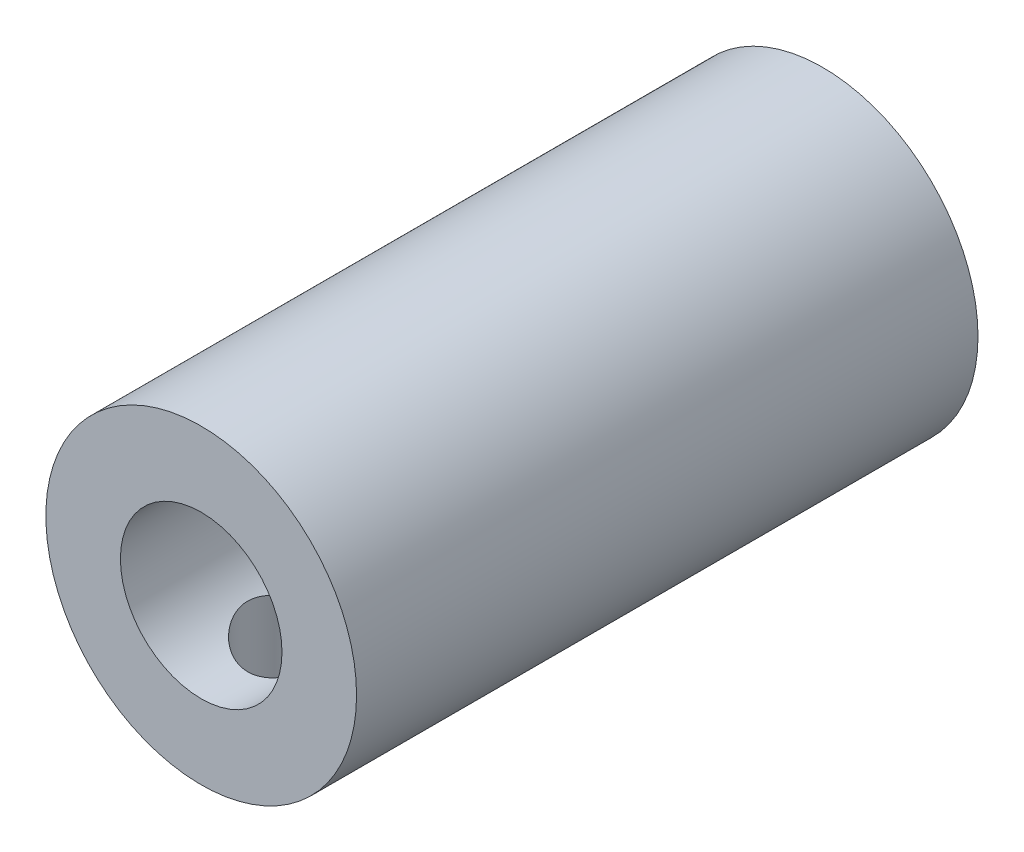
SolidWorks part; units mm, degrees
ref_plane "Front Plane" through (0, 0, 0) normal (0, 0, 1) x (1, 0, 0)
ref_plane "Top Plane" through (0, 0, 0) normal (0, 1, 0) x (1, 0, 0)
ref_plane "Right Plane" through (0, 0, 0) normal (1, 0, 0) x (0, 0, -1)
sketch "Sketch1" plane through (0, 0, 0) normal (0, 0, 1) x (1, 0, 0)
  line L0 (-100.533, 0) -> (100.533, 0) construction
  circle A0 centre (0, 0) radius 10
  point P4 (0, 0)
extrude "Boss-Extrude1" add sketch "Sketch1" along normal mid plane 40
sketch "Sketch5" plane through (0, 0, 0) normal (0, 0, 1) x (1, 0, 0)
  circle A0 centre (0, 0) radius 8
extrude "Cut-Extrude2" cut sketch "Sketch5" against normal blind 25
sketch "Sketch6" plane through (0, 0, 0) normal (0, 0, 1) x (1, 0, 0)
  circle A0 centre (0, 0) radius 5.2
extrude "Cut-Extrude3" cut sketch "Sketch6" along normal blind 25
sketch "Sketch7" plane through (0, 0, 0) normal (0, 1, 0) x (1, 0, 0)
  line L0 (0, 22.3968) -> (0, -22.3968) construction
  line L1 (8, 20) -> (-8, 20) construction
  line L2 (-10, -20) -> (10, -20) construction
  circle A0 centre (0, 14) radius 3
  circle A1 centre (0, -14) radius 3
  point P4 (0, 0)
  dimension "D1" = 6
  dimension "D2" = 6
extrude "Cut-Extrude4" cut sketch "Sketch7" against normal blind 10 contours A0 | A1
